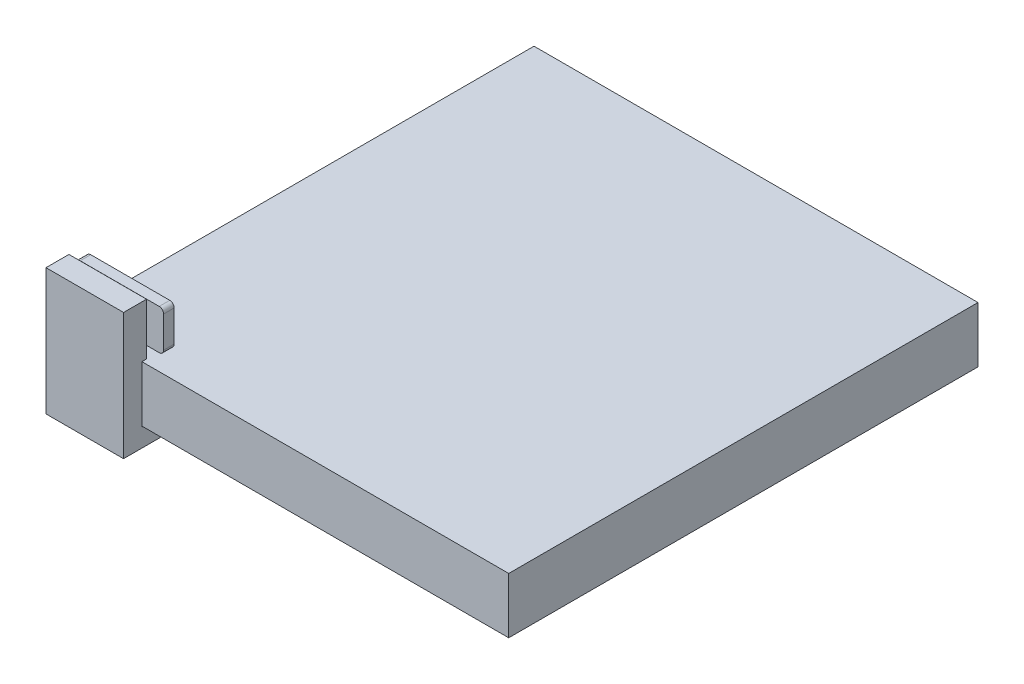
SolidWorks part; units mm, degrees
ref_plane "Front Plane" through (0, 0, 0) normal (0, 0, 1) x (1, 0, 0)
ref_plane "Top Plane" through (0, 0, 0) normal (0, 1, 0) x (1, 0, 0)
ref_plane "Right Plane" through (0, 0, 0) normal (1, 0, 0) x (0, 0, -1)
sketch "Sketch1" plane through (0, 0, 0) normal (0, 1, 0) x (1, 0, 0)
  line L1 (0, 0) -> (303.3879, 0)
  line L2 (0, 0) -> (0, 320.675)
  line L3 (0, 320.675) -> (303.3879, 320.675)
  line L4 (303.3879, 0) -> (303.3879, 320.675)
  line L5 (82.5065, 317.5) -> (234.9471, 317.5)
  line L6 (82.5065, 317.5) -> (82.5065, 3.175)
  line L7 (82.5065, 3.175) -> (234.9471, 3.175)
  line L8 (234.9471, 317.5) -> (234.9471, 3.175)
  point P9 (234.9471, 160.3375)
  point P10 (303.3879, 160.3375)
  dimension "D1" = 320.675
  dimension "D2" = 314.325
extrude "Boss-Extrude1" add sketch "Sketch1" against normal blind 38.1 contours L2 L1 L4 L3
sketch "Sketch3" plane through (0, 0, 0) normal (1, 0, 0) x (0, 0, -1)
  line L0 (0, -38.1) -> (320.675, -38.1) construction
  line L1 (24.7, -38.4) -> (-0.3, -38.4)
  line L2 (24.7, -38.4) -> (24.7, -50.9)
  line L3 (24.7, -50.9) -> (-12.8, -50.9)
  line L6 (-12.8, -50.9) -> (-12.8, 35.6614)
  line L7 (-12.8, 35.6614) -> (-0.3, 35.6614)
  line L8 (-0.3, -38.4) -> (-0.3, 0.3)
  line L9 (0, -38.1) -> (0, 0) construction
  line L10 (0, 0) -> (320.675, 0) construction
  line L11 (-0.3, 35.6614) -> (2.875, 35.6614)
  line L13 (-0.3, 0.3) -> (2.875, 0.3)
  line L14 (2.875, 35.6614) -> (2.875, 0.3)
  dimension "D1" = 0.3
  dimension "D2" = 0.3
  dimension "D3" = 12.5
  dimension "D4" = 12.5
  dimension "D5" = 0.3
  dimension "D6" = 0.3
  dimension "D7" = 86.5614
  dimension "D9" = 25
extrude "Boss-Extrude2" add sketch "Sketch3" along normal blind 53 separate body
sketch "Sketch2" plane through (0, 0, 0) normal (0, 0, 1) x (1, 0, 0)
  line L3 (0, -38.1) -> (303.3879, -38.1) construction
  line L4 (82.5065, 0) -> (234.9471, 0) construction
  line L5 (14.575, 20.35) -> (38.425, 19.5) construction
  line L6 (53, 35.6614) -> (0, 35.6614) construction
  circle A0 centre (14.575, 20.35) radius 8.35
  circle A1 centre (38.425, 19.5) radius 7.5
  point P11 (26.5, 35.6614)
  point P12 (26.5, 19.925)
  dimension "D1" = 16.7
  dimension "D2" = 15
  dimension "D3" = 50.1
  dimension "D5" = 8
  dimension "D4" = 50.1
extrude "Boss-Extrude4" add sketch "Sketch2" against normal blind 12.5 from surface at -2.875 starting at face at (26.5, 17.9807, -2.875)
sketch "Sketch4" plane through (53, 0, 0) normal (1, 0, 0) x (0, 0, -1)
  line L0 (2.875, 12) -> (15.375, 12) construction
  line L1 (4.575, 28.7) -> (12.075, 28.7)
  line L2 (4.575, 28.7) -> (4.575, 25.85)
  line L3 (4.575, 25.85) -> (12.075, 25.85)
  line L4 (12.075, 28.7) -> (12.075, 25.85)
  line L5 (4.575, 12) -> (12.075, 12)
  line L6 (4.575, 12) -> (4.575, 14.85)
  line L7 (4.575, 14.85) -> (12.075, 14.85)
  line L8 (12.075, 12) -> (12.075, 14.85)
  line L9 (15.375, 28.7) -> (2.875, 28.7) construction
  line L10 (4.375, 28.7) -> (2.875, 28.7) construction
  dimension "D1" = 1.5
  dimension "D2" = 0.2
  dimension "D3" = 7.5
  dimension "D4" = 11
extrude "Cut-Extrude1" cut sketch "Sketch4" against normal through all
sketch "Sketch5" plane through (0, 0, -4.575) normal (0, 0, -1) x (-1, 0, 0)
  line L0 (-34.4341, 25.85) -> (-42.4159, 25.85) construction
  line L2 (-63, 31.05) -> (-63, 9.65)
  line L4 (-46.425, 23.05) -> (-46.425, 17.65)
  line L5 (-60, 34.05) -> (-6, 34.05)
  line L6 (-63, 31.05) -> (-63, 25.1254)
  line L7 (-43.425, 26.05) -> (-6, 26.05)
  line L8 (-3, 31.05) -> (-3, 29.05)
  line L9 (-60, 6.65) -> (-6, 6.65)
  line L10 (-63, 9.65) -> (-63, 11.496)
  line L11 (-43.425, 14.65) -> (-6, 14.65)
  line L12 (-3, 9.65) -> (-3, 11.65)
  line L13 (-32.5405, 14.85) -> (-44.3095, 14.85) construction
  line L14 (0, 0.3) -> (0, 35.6614) construction
  line L15 (-53, 0.3) -> (-53, 35.6614) construction
  circle A3 centre (-38.425, 19.5) radius 7.5 construction
  arc A4 (-6, 34.05) -> (-3, 31.05) centre (-6, 31.05) cw
  arc A5 (-6, 26.05) -> (-3, 29.05) centre (-6, 29.05) ccw
  arc A6 (-6, 6.65) -> (-3, 9.65) centre (-6, 9.65) ccw
  arc A7 (-6, 14.65) -> (-3, 11.65) centre (-6, 11.65) cw
  arc A8 (-43.425, 14.65) -> (-46.425, 17.65) centre (-43.425, 17.65) cw
  arc A9 (-46.425, 23.05) -> (-43.425, 26.05) centre (-43.425, 23.05) cw
  arc A10 (-63, 9.65) -> (-60, 6.65) centre (-60, 9.65) ccw
  arc A11 (-60, 34.05) -> (-63, 31.05) centre (-60, 31.05) ccw
  point P0 (-63, 11.496)
  point P24 (-3, 34.05)
  point P27 (-3, 26.05)
  arc M9 (-34.4341, 25.85) -> (-42.4159, 25.85) centre (-38.425, 19.5) ccw
  dimension "D7" = 3
  dimension "D1" = 0.2
  dimension "D2" = 0.2
  dimension "D3" = 3
  dimension "D4" = 8
  dimension "D5" = 0.5
  dimension "D6" = 10
  dimension "D9" = 0.7246
  dimension "D10" = 14.354
extrude "Boss-Extrude11" add sketch "Sketch5" along direction (0, 0, 1) on the side of the normal offset from surface (7.2 mm away) 0.3 separate body contours L7 M9 | L5 A11 L2 A10 L9 A6 L12 A7 L11 A8 L4 A9 L7 A5 L8 A4 M9
sketch "Sketch6" plane through (0, 0, -11.775) normal (0, 0, -1) x (-1, 0, 0)
  line L0 (-55, 26.35) -> (-55, 14.35) construction
  line L1 (-51, 26.35) -> (-51, 14.35)
  line L2 (-59, 26.35) -> (-59, 14.35)
  line L3 (-46.425, 23.05) -> (-46.425, 17.65) construction
  line L4 (-63, 31.05) -> (-63, 9.65) construction
  arc A0 (-51, 26.35) -> (-59, 26.35) centre (-55, 26.35) ccw
  arc A1 (-59, 14.35) -> (-51, 14.35) centre (-55, 14.35) ccw
  point P2 (-55, 20.35)
  point P9 (-46.425, 20.35)
  dimension "D2" = 4
  dimension "D1" = 12
  dimension "D3" = 8
extrude "Cut-Extrude2" cut sketch "Sketch6" against normal blind 3
